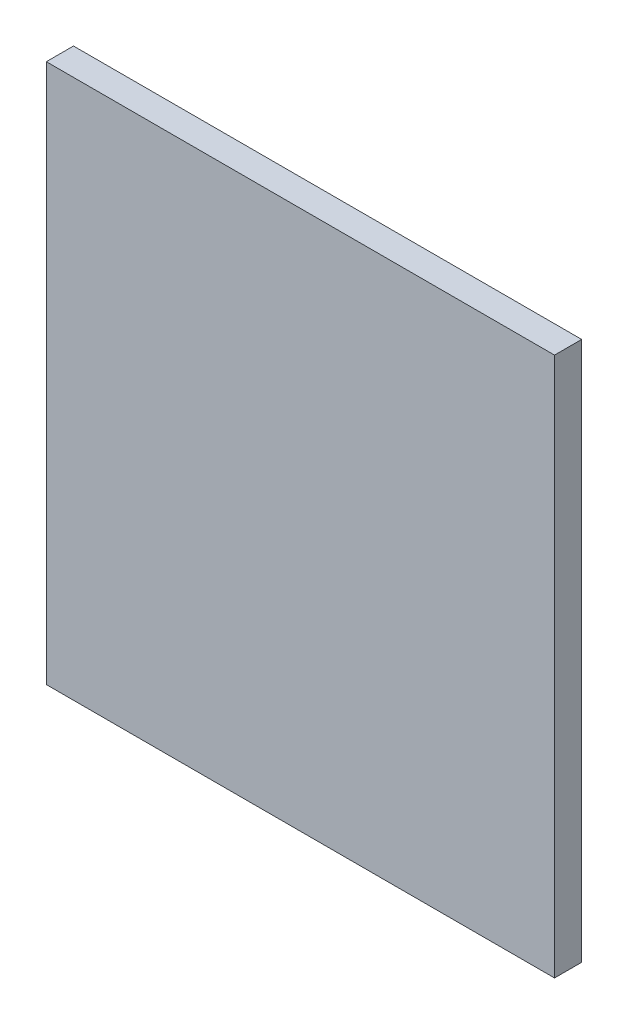
SolidWorks part; units mm, degrees
ref_plane "Alzado" through (0, 0, 0) normal (0, 0, 1) x (1, 0, 0)
ref_plane "Planta" through (0, 0, 0) normal (0, 1, 0) x (1, 0, 0)
ref_plane "Vista lateral" through (0, 0, 0) normal (1, 0, 0) x (0, 0, -1)
sketch "Croquis1" plane through (0, 0, 0) normal (0, 0, 1) x (1, 0, 0)
  line L1 (-90.9615, 34.8077) -> (-25.4615, 34.8077)
  line L2 (-90.9615, 34.8077) -> (-90.9615, -39.1923)
  line L3 (-90.9615, -39.1923) -> (-25.4615, -39.1923)
  line L4 (-25.4615, 34.8077) -> (-25.4615, -39.1923)
  dimension "D1" = 65.5
  dimension "D2" = 74
extrude "Saliente-Extruir1" add sketch "Croquis1" along normal blind 1.8
sketch "Croquis2" plane through (0, 0, 1.8) normal (0, 0, 1) x (1, 0, 0)
  line L0 (-90.9615, -39.1923) -> (-25.4615, -39.1923) construction
  line L1 (-90.9615, 34.8077) -> (-85.9615, 34.8077)
  line L2 (-90.9615, 34.8077) -> (-90.9615, -39.1923)
  line L3 (-90.9615, -39.1923) -> (-85.9615, -39.1923)
  line L4 (-85.9615, 34.8077) -> (-85.9615, -39.1923)
  line L6 (-25.4615, 34.8077) -> (-30.4615, 34.8077)
  line L7 (-25.4615, 34.8077) -> (-25.4615, -39.1923)
  line L8 (-25.4615, -39.1923) -> (-30.4615, -39.1923)
  line L9 (-30.4615, 34.8077) -> (-30.4615, -39.1923)
  dimension "D1" = 5
  dimension "D2" = 5
extrude "Saliente-Extruir2" add sketch "Croquis2" along normal blind 15
sketch "Croquis3" plane through (0, -39.1923, 0) normal (0, -1, 0) x (1, 0, 0)
  line L0 (-88.4615, 16.8) -> (-89.1115, 16.8)
  line L1 (-90.9615, 16.8) -> (-85.9615, 16.8) construction
  line L2 (-89.1115, 16.8) -> (-89.1115, 15.9)
  line L3 (-89.1115, 15.9) -> (-87.8115, 15.9)
  line L4 (-87.8115, 15.9) -> (-87.8115, 16.8)
  line L5 (-87.8115, 16.8) -> (-88.4615, 16.8)
  line L6 (-88.4615, 15.9) -> (-88.4615, 15) construction
  line L7 (-90.9615, 15) -> (-89.3615, 15) construction
  line L8 (-90.9615, 16.8) -> (-90.9615, 0) construction
  line L9 (-85.9615, 16.8) -> (-85.9615, 1.8) construction
  line L10 (-89.3615, 15) -> (-85.9615, 15)
  line L11 (-89.3615, 15) -> (-89.3615, 12.9)
  line L12 (-89.3615, 12.9) -> (-85.9615, 12.9)
  line L13 (-85.9615, 15) -> (-85.9615, 12.9)
  line L14 (-58.2115, 1.8) -> (-58.2115, 0) construction
  line L15 (-85.9615, 1.8) -> (-30.4615, 1.8) construction
  line L16 (-90.9615, 0) -> (-25.4615, 0) construction
  line L17 (-25.4615, 15) -> (-27.0615, 15) construction
  line L18 (-27.9615, 15.9) -> (-27.9615, 15) construction
  line L19 (-30.4615, 15) -> (-30.4615, 12.9)
  line L20 (-27.0615, 12.9) -> (-30.4615, 12.9)
  line L21 (-27.0615, 15) -> (-27.0615, 12.9)
  line L22 (-27.0615, 15) -> (-30.4615, 15)
  line L23 (-28.6115, 16.8) -> (-27.9615, 16.8)
  line L24 (-28.6115, 15.9) -> (-28.6115, 16.8)
  line L25 (-27.3115, 15.9) -> (-28.6115, 15.9)
  line L26 (-27.3115, 16.8) -> (-27.3115, 15.9)
  line L27 (-27.9615, 16.8) -> (-27.3115, 16.8)
  dimension "D1" = 1.3
  dimension "D2" = 0.9
  dimension "D3" = 1.6
  dimension "D4" = 0.9
  dimension "D5" = 2.1
extrude "Cortar-Extruir1" cut sketch "Croquis3" against normal up to vertex (74 mm away)
sketch "Croquis4" plane through (0, -39.1923, 0) normal (0, -1, 0) x (1, 0, 0)
  line L5 (-28.6115, 15.9) -> (-27.3115, 15.9)
  line L6 (-28.6115, 15.9) -> (-28.6115, 17.7)
  line L7 (-28.6115, 17.7) -> (-27.3115, 17.7)
  line L8 (-27.3115, 15.9) -> (-27.3115, 17.7)
  dimension "D1" = 1.8
sketch "Croquis6" plane through (0, -39.1923, 0) normal (0, -1, 0) x (1, 0, 0)
  line L0 (-85.9615, 12.9) -> (-85.9615, 8.7) construction
  line L1 (-85.9615, 12.9) -> (-85.9615, 1.8) construction
  line L2 (-85.9615, 1.8) -> (-30.4615, 1.8) construction
  line L3 (-85.9615, 8.7) -> (-80.9615, 8.7)
  line L6 (-80.9615, 8.7) -> (-80.9615, 1.8)
  line L7 (-30.4615, 12.9) -> (-30.4615, 1.8) construction
  line L8 (-30.4615, 5.7) -> (-45.4615, 5.7)
  line L11 (-45.4615, 5.7) -> (-45.4615, 1.8)
  line L12 (-85.9615, 8.7) -> (-90.9615, 8.7)
  line L13 (-90.9615, 16.8) -> (-90.9615, 0) construction
  line L14 (-90.9615, 8.7) -> (-90.9615, 0)
  line L15 (-90.9615, 0) -> (-25.4615, 0)
  line L16 (-25.4615, 0) -> (-25.4615, 5.7)
  line L17 (-25.4615, 16.8) -> (-25.4615, 0) construction
  line L18 (-25.4615, 5.7) -> (-30.4615, 5.7)
  line L19 (-80.9615, 1.8) -> (-45.4615, 1.8)
  dimension "D1" = 4.2
  dimension "D2" = 5
  dimension "D3" = 15
extrude "Saliente-Extruir4" add sketch "Croquis6" along normal blind 1.8
sketch "Croquis7" plane through (0, 0, 0) normal (0, 0, -1) x (-1, 0, 0)
  line L0 (58.2115, -40.9923) -> (58.2115, 34.8077) construction
  line L1 (90.9615, -40.9923) -> (25.4615, -40.9923) construction
  line L2 (25.4615, 34.8077) -> (90.9615, 34.8077) construction
  line L4 (51.2115, -14.5923) -> (65.2115, -14.5923)
  line L5 (51.2115, -14.5923) -> (51.2115, 8.4077)
  line L6 (51.2115, 8.4077) -> (65.2115, 8.4077)
  line L7 (65.2115, -14.5923) -> (65.2115, 8.4077)
  line L8 (51.2115, -14.5923) -> (65.2115, 8.4077) construction
  line L9 (51.2115, 8.4077) -> (65.2115, -14.5923) construction
  point P6 (58.2115, -3.0923)
  dimension "D1" = 14
  dimension "D2" = 23
extrude "Saliente-Extruir5" add sketch "Croquis7" along normal blind 3
sketch "Croquis9" plane through (0, -14.5923, 0) normal (0, -1, 0) x (1, 0, 0)
  line L0 (-51.2115, -3) -> (-54.2115, 0)
  line L1 (-51.2115, 0) -> (-65.2115, 0) construction
  line L2 (-54.2115, 0) -> (-51.2115, 0)
  line L3 (-51.2115, 0) -> (-51.2115, -3)
  line L4 (-65.2115, -3) -> (-62.2115, 0)
  line L5 (-62.2115, 0) -> (-65.2115, 0)
  line L6 (-65.2115, 0) -> (-65.2115, -3)
  dimension "D1" = 45
extrude "Cortar-Extruir5" cut sketch "Croquis9" against normal up to vertex (23 mm away)
sketch "Croquis10" plane through (0, -39.1923, 0) normal (0, -1, 0) x (1, 0, 0)
  line L0 (-87.6615, 12.9) -> (-87.6615, 10.9) construction
  line L1 (-89.3615, 12.9) -> (-85.9615, 12.9) construction
  line L2 (-28.7615, 12.9) -> (-28.7615, 10.9) construction
  line L3 (-30.4615, 12.9) -> (-27.0615, 12.9) construction
  circle A0 centre (-87.6615, 10.9) radius 1
  circle A1 centre (-28.7615, 10.9) radius 1
extrude "Cortar-Extruir6" cut sketch "Croquis10" against normal blind 8
sketch "Croquis11" plane through (0, 34.8077, 0) normal (0, 1, 0) x (1, 0, 0)
  line L0 (-28.7615, -12.9) -> (-28.7615, -10.9) construction
  line L1 (-30.4615, -12.9) -> (-27.0615, -12.9) construction
  line L2 (-87.6615, -12.9) -> (-87.6615, -10.9) construction
  line L3 (-89.3615, -12.9) -> (-85.9615, -12.9) construction
  circle A0 centre (-28.7615, -10.9) radius 1
  circle A1 centre (-87.6615, -10.9) radius 1
extrude "Cortar-Extruir7" cut sketch "Croquis11" against normal blind 8
sketch "Croquis12" plane through (0, 0, -3) normal (0, 0, -1) x (-1, 0, 0)
  line L1 (74.5987, -19.3989) -> (40.9214, -19.3989)
  line L2 (74.5987, -19.3989) -> (74.5987, 16.3489)
  line L3 (74.5987, 16.3489) -> (40.9214, 16.3489)
  line L4 (40.9214, -19.3989) -> (40.9214, 16.3489)
  line L5 (93.3878, 36.1683) -> (21.3475, 36.1683)
  line L6 (93.3878, 36.1683) -> (93.3878, -44.7695)
  line L7 (93.3878, -44.7695) -> (21.3475, -44.7695)
  line L8 (21.3475, 36.1683) -> (21.3475, -44.7695)
extrude "Cortar-Extruir8" cut sketch "Croquis12" against normal up to vertex
